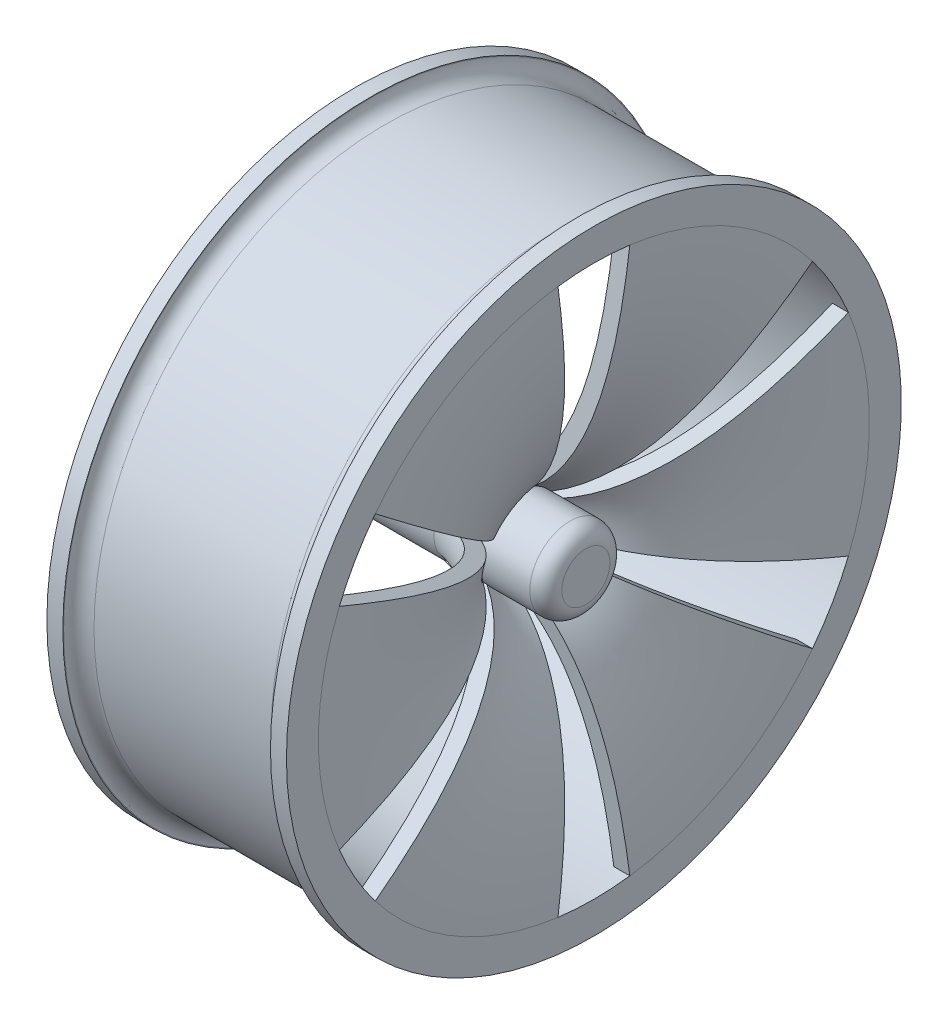
SolidWorks part; units mm, degrees
ref_plane "Front Plane" through (0, 0, 0) normal (0, 0, 1) x (1, 0, 0)
ref_plane "Top Plane" through (0, 0, 0) normal (0, 1, 0) x (1, 0, 0)
ref_plane "Right Plane" through (0, 0, 0) normal (1, 0, 0) x (0, 0, -1)
sketch "Sketch1" plane through (0, 0, 0) normal (0, 0, 1) x (1, 0, 0)
  line L0 (0, 0) -> (196.5854, 0) construction
  line L1 (0, 0) -> (0, 171.7073) construction
  line L2 (-15, 34.5) -> (13, 34.5)
  line L3 (15, 34.5) -> (15, 38.5)
  line L4 (15, 38.5) -> (13, 38.5)
  line L5 (13, 38.5) -> (13, 38.4)
  line L6 (11.1, 36.5) -> (-11.1, 36.5)
  line L7 (-13, 38.5) -> (-13, 38.4)
  line L8 (-15, 38.5) -> (-13, 38.5)
  line L9 (-15, 34.5) -> (-15, 38.5)
  line L10 (15, 18.0454) -> (15, 23.9546) construction
  line L11 (0, 3) -> (0, 5.0201)
  arc A0 (13, 38.4) -> (11.1, 36.5) centre (11.1, 38.4) cw
  arc A1 (-13, 38.4) -> (-11.1, 36.5) centre (-11.1, 38.4) ccw
  spline S0 degree 3 poles (15, 34.5) (15, 25.7789) (14.4697, 4.9168) (0, 3) knots 0 0 0 0 1 1 1 1
  spline S1 degree 1 poles (13, 34.5) (-0.2626, 4.9827) knots 0 0 1 1 construction
  spline S2 degree 3 poles (13, 34.5) (13, 34.2192) (12.999, 33.6727) (12.9896, 32.4585) (12.9583, 30.8131) (12.8702, 28.6511) (12.6606, 25.589) (12.1792, 21.5367) (11.1105, 16.698) (9.4311, 12.2738) (7.4634, 9.2525) (5.5258, 7.3735) (3.8746, 6.2483) (2.2948, 5.5585) (0.9929, 5.1985) (0.2998, 5.0659) (-0.0865, 5.0068) (-0.1984, 4.9912) (-0.2626, 4.9827) knots 0 0 0 0 0.03125 0.0625 0.125 0.1875 0.25 0.375 0.5 0.625 0.75 0.8125 0.875 0.9375 0.96875 0.991244 0.994746 1 1 1 1 only from (13, 34.5) to (0, 5.0201)
  point P14 (0, 36.5)
  point P19 (0, 34.5)
  dimension "D6" = 1.9
  dimension "D1" = 15
  dimension "D2" = 34.5
  dimension "D3" = 4
  dimension "D4" = 2
  dimension "D5" = 2
  dimension "D7" = 36.5
  dimension "D8" = 3
  dimension "D9" = 11.5
  dimension "D10" = 2
revolve "Revolve4" add sketch "Sketch1" angle 360 about L0
sketch "Sketch2" plane through (-15, 0, 0) normal (-1, 0, 0) x (0, 0, 1)
  circle A0 centre (0, 0) radius 3 construction
  circle A1 centre (0, 0) radius 3
  circle A2 centre (0, 0) radius 5.0201 construction
  circle A3 centre (0, 0) radius 5.0201
extrude "Boss-Extrude1" add sketch "Sketch2" against normal blind 29
sketch "Sketch3" plane through (14, 0, 0) normal (1, 0, 0) x (0, 0, -1)
  circle A1 centre (0, 0) radius 5.0201
  circle A2 centre (0, 0) radius 5.0201
  dimension "D1" = 0
extrude "Boss-Extrude3" add sketch "Sketch3" against normal blind 2
sketch "Sketch4" plane through (15, 0, 0) normal (1, 0, 0) x (0, 0, -1)
  line L0 (-0.6548, 4.9772) -> (-4.5, 34.2053)
  line L1 (0.6548, 4.9772) -> (4.5, 34.2053)
  circle A0 centre (0, 0) radius 34.5 construction
  circle A1 centre (0, 0) radius 5.0201
  arc A2 (0.6548, 4.9772) -> (-0.6548, 4.9772) centre (0, 0) ccw
  circle A3 centre (0, 0) radius 34.5
  circle M6 centre (0, 0) radius 34.5
  dimension "D2" = 9
  dimension "D1" = 0
extrude "Cut-Extrude1" cut sketch "Sketch4" against normal through all contours A2 L1 L0 M6
pattern_circular "CirPattern1" count 6 over 360 about axis through (0, 0, 0) along (1, 0, 0) of "Cut-Extrude1"
fillet "Fillet3" radius 2 1 edges at (14, 0, 5.0201)
